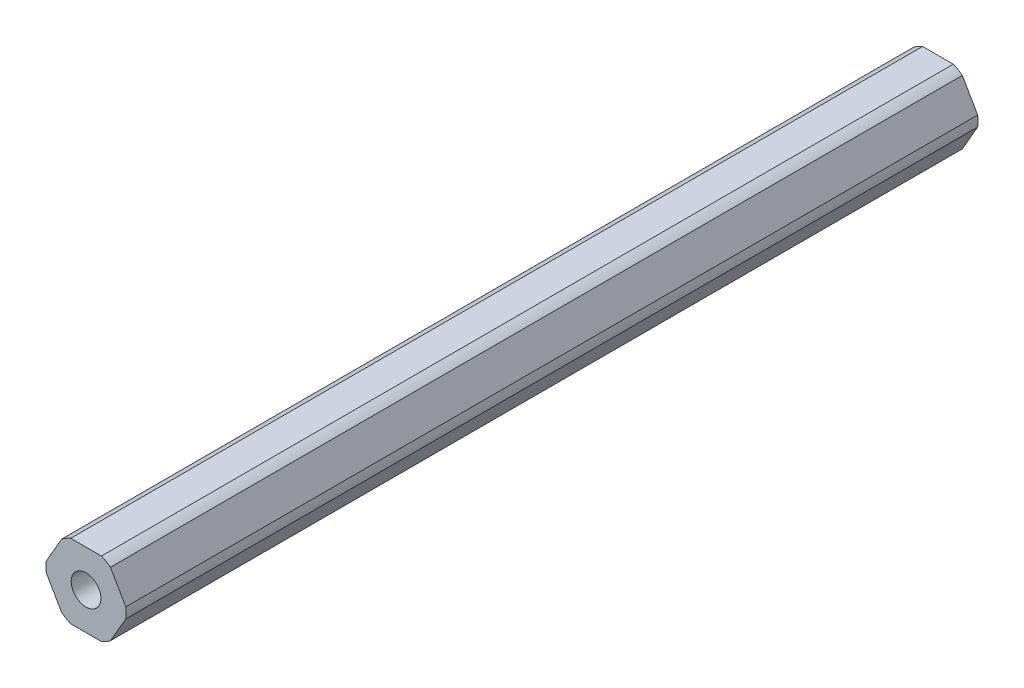
SolidWorks part; units mm, degrees
ref_plane "Front Plane" through (0, 0, 0) normal (0, 0, 1) x (1, 0, 0)
ref_plane "Top Plane" through (0, 0, 0) normal (0, 1, 0) x (1, 0, 0)
ref_plane "Right Plane" through (0, 0, 0) normal (1, 0, 0) x (0, 0, -1)
sketch "Sketch1" plane through (0, 0, 0) normal (0, 0, 1) x (1, 0, 0)
  line L1 (2.635, 6.35) -> (-2.635, 6.35)
  line L2 (-4.1818, 5.457) -> (-6.8168, 0.893)
  line L3 (-6.8168, -0.893) -> (-4.1818, -5.457)
  line L4 (-2.635, -6.35) -> (2.635, -6.35)
  line L5 (4.1818, -5.457) -> (6.8168, -0.893)
  line L6 (6.8168, 0.893) -> (4.1818, 5.457)
  circle A0 centre (0, 0) radius 6.35 construction
  arc A1 (-2.635, 6.35) -> (-4.1818, 5.457) centre (0, 0) ccw
  arc A2 (4.1818, 5.457) -> (2.635, 6.35) centre (0, 0) ccw
  arc A3 (6.8168, -0.893) -> (6.8168, 0.893) centre (0, 0) ccw
  arc A4 (2.635, -6.35) -> (4.1818, -5.457) centre (0, 0) ccw
  arc A5 (-4.1818, -5.457) -> (-2.635, -6.35) centre (0, 0) ccw
  arc A6 (-6.8168, 0.893) -> (-6.8168, -0.893) centre (0, 0) ccw
  circle A7 centre (0, 0) radius 2.55
  dimension "D1" = 12.7
  dimension "D2" = 13.75
  dimension "D3" = 5.1
extrude "Boss-Extrude1" add sketch "Sketch1" along normal blind 146.05
